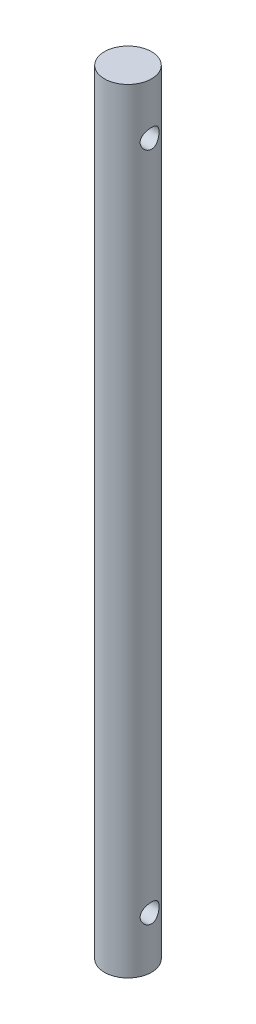
SolidWorks part; units mm, degrees
ref_plane "Front Plane" through (0, 0, 0) normal (0, 0, 1) x (1, 0, 0)
ref_plane "Top Plane" through (0, 0, 0) normal (0, 1, 0) x (1, 0, 0)
ref_plane "Right Plane" through (0, 0, 0) normal (1, 0, 0) x (0, 0, -1)
sketch "Sketch1" plane through (0, 0, 0) normal (0, 1, 0) x (1, 0, 0)
  circle A0 centre (0, 0) radius 3.9624
extrude "Boss-Extrude1" add sketch "Sketch1" along normal mid plane 130.175
sketch "Sketch2" plane through (0, 0, 0) normal (0, 0, 1) x (1, 0, 0)
  line L0 (3.9624, 65.0875) -> (-3.9624, 65.0875) construction
  line L1 (-15.4457, 58.0136) -> (15.1627, 58.0136)
  line L2 (-15.4457, 58.0136) -> (-15.4457, 56.4261)
  line L3 (-15.4457, 56.4261) -> (15.1627, 56.4261)
  line L4 (15.1627, 58.0136) -> (15.1627, 56.4261)
  dimension "D1" = 1.5875
  dimension "D2" = 8.6614
revolve "Cut-Revolve1" cut sketch "Sketch2" angle 360 about L3
mirror "Mirror1" about plane through (0, 0, 0) normal (0, 1, 0) of "Cut-Revolve1"
